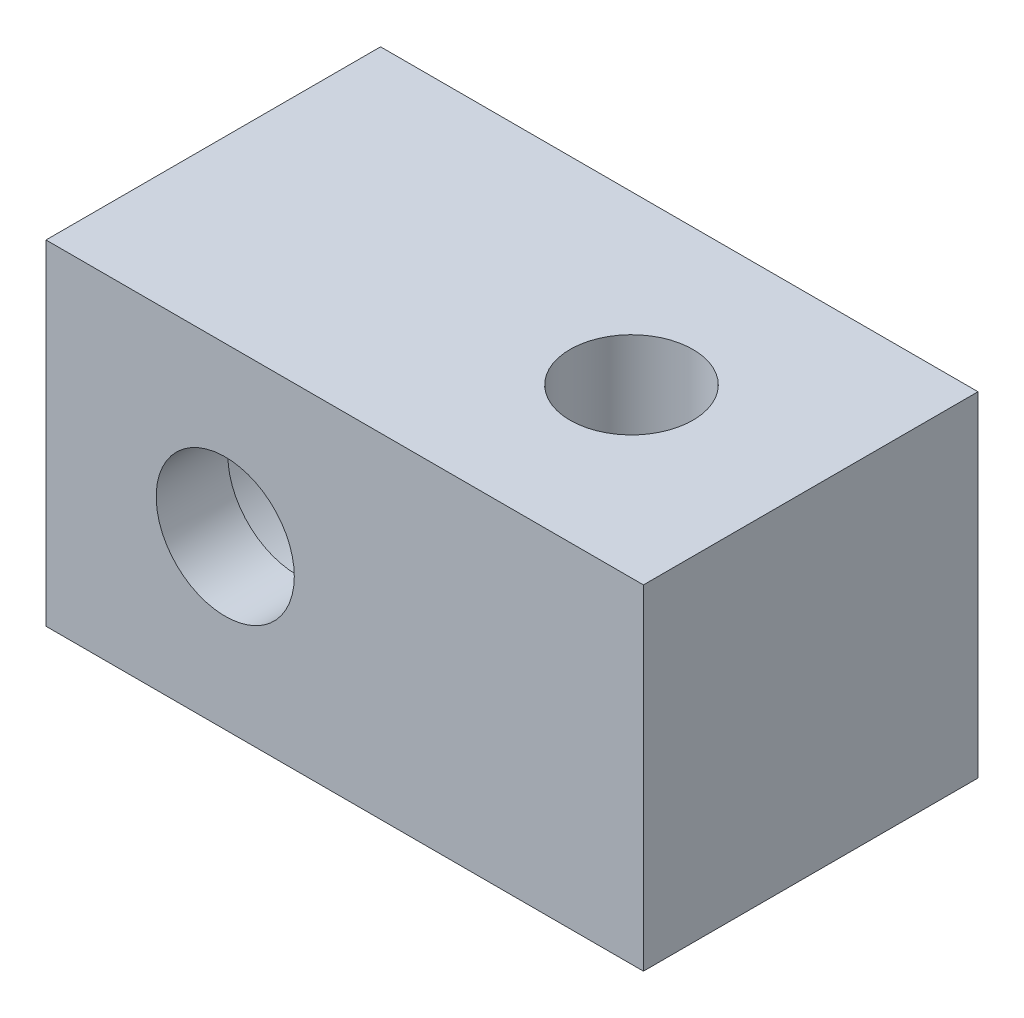
SolidWorks part; units mm, degrees
ref_plane "Front Plane" through (0, 0, 0) normal (0, 0, 1) x (1, 0, 0)
ref_plane "Top Plane" through (0, 0, 0) normal (0, 1, 0) x (1, 0, 0)
ref_plane "Right Plane" through (0, 0, 0) normal (1, 0, 0) x (0, 0, -1)
sketch "Sketch1" plane through (0, 0, 0) normal (0, 1, 0) x (1, 0, 0)
  line L1 (-15.875, 8.89) -> (15.875, 8.89)
  line L2 (-15.875, 8.89) -> (-15.875, -8.89)
  line L3 (-15.875, -8.89) -> (15.875, -8.89)
  line L4 (15.875, 8.89) -> (15.875, -8.89)
  line L5 (-15.875, 8.89) -> (15.875, -8.89) construction
  line L6 (-15.875, -8.89) -> (15.875, 8.89) construction
  point P0 (0, 0)
  dimension "D1" = 17.78
  dimension "D2" = 31.75
extrude "Boss-Extrude1" add sketch "Sketch1" along normal blind 17.78
sketch "Sketch2" plane through (0, 0, 8.89) normal (0, 0, 1) x (1, 0, 0)
  line L0 (-15.875, 8.89) -> (15.875, 8.89) construction
  line L1 (-15.875, 17.78) -> (-15.875, 0) construction
  line L2 (15.875, 17.78) -> (15.875, 0) construction
  line L3 (0, 17.78) -> (0, 0) construction
  line L4 (-15.875, 17.78) -> (15.875, 17.78) construction
  circle A0 centre (-6.35, 8.89) radius 3.6703
  dimension "D1" = 7.3406
  dimension "D2" = 6.35
sketch "Sketch3" plane through (0, 0, -8.89) normal (0, 0, -1) x (-1, 0, 0)
  circle A0 centre (6.35, 8.89) radius 6.4389
  dimension "D1" = 12.8778
extrude "Cut-Extrude1" cut sketch "Sketch3" against normal blind 13.97
extrude "Cut-Extrude2" cut sketch "Sketch2" against normal up to next
hole_wizard "1/4 Clearance Hole1" positions "Sketch5" profile "Sketch6" hole size "1/4" standard "ANSI Inch" end condition through all
sketch "Sketch5" plane through (0, 17.78, 0) normal (0, 1, 0) x (1, 0, 0)
  line L0 (-15.875, 0) -> (15.875, 0) construction
  line L1 (-15.875, 8.89) -> (-15.875, -8.89) construction
  line L2 (15.875, -8.89) -> (15.875, 8.89) construction
  point P8 (6.35, 0)
  dimension "D1" = 6.35
sketch "Sketch6" plane through (6.35, 17.78, 0) normal (1, 0, 0) x (0, 0, 1)
  line L0 (0, 0) -> (0, 17.78)
  line L1 (0, 17.78) -> (3.2639, 17.78)
  line L2 (3.2639, 17.78) -> (3.2639, 0)
  line L5 (3.2639, 0) -> (0, 0)
  line L11 (0, -6.35) -> (0, 107.95) construction
  dimension "Thru Hole Dia." = 6.5278
  dimension "Thru Hole Depth" = 17.78
